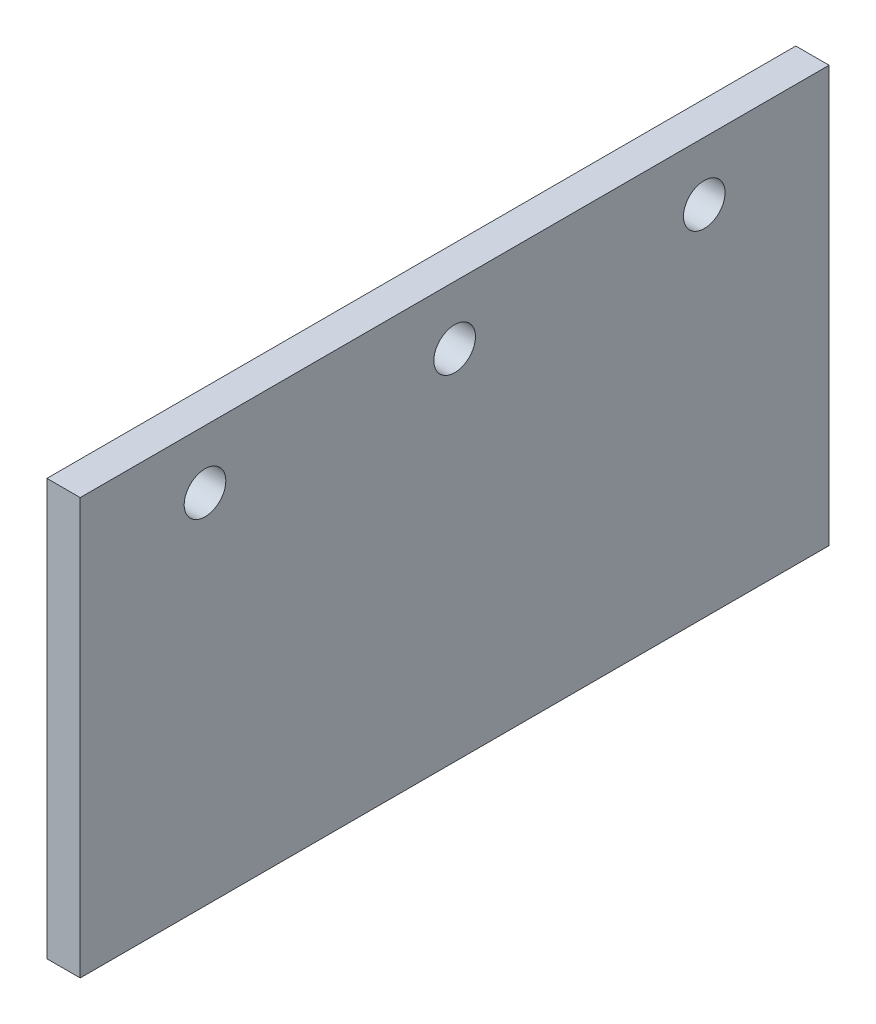
SolidWorks part; units mm, degrees
ref_plane "Front Plane" through (0, 0, 0) normal (0, 0, 1) x (1, 0, 0)
ref_plane "Top Plane" through (0, 0, 0) normal (0, 1, 0) x (1, 0, 0)
ref_plane "Right Plane" through (0, 0, 0) normal (1, 0, 0) x (0, 0, -1)
sketch "Sketch1" plane through (0, 0, 0) normal (1, 0, 0) x (0, 0, -1)
  line L1 (0, 0) -> (90, 0)
  line L2 (0, 0) -> (0, -50)
  line L3 (0, -50) -> (90, -50)
  line L4 (90, 0) -> (90, -50)
  dimension "D1" = 90
  dimension "D2" = 50
extrude "Boss-Extrude1" add sketch "Sketch1" along normal blind 4
sketch "Sketch2" plane through (4, 0, 0) normal (1, 0, 0) x (0, 0, -1)
  line L0 (90, -50) -> (90, 0) construction
  line L1 (0, 2.2) -> (0, -2.2) construction
  line L2 (2.2, 0) -> (-2.2, 0) construction
  circle A0 centre (15, -7) radius 2.5
  circle A1 centre (45, -7) radius 2.5
  circle A2 centre (75, -7) radius 2.5
  dimension "D7" = 5
  dimension "D1" = 45
  dimension "D2" = 15
  dimension "D3" = 15
  dimension "D4" = 7
  dimension "D5" = 7
  dimension "D6" = 7
extrude "Cut-Extrude1" cut sketch "Sketch2" against normal through all both and the other way through all
